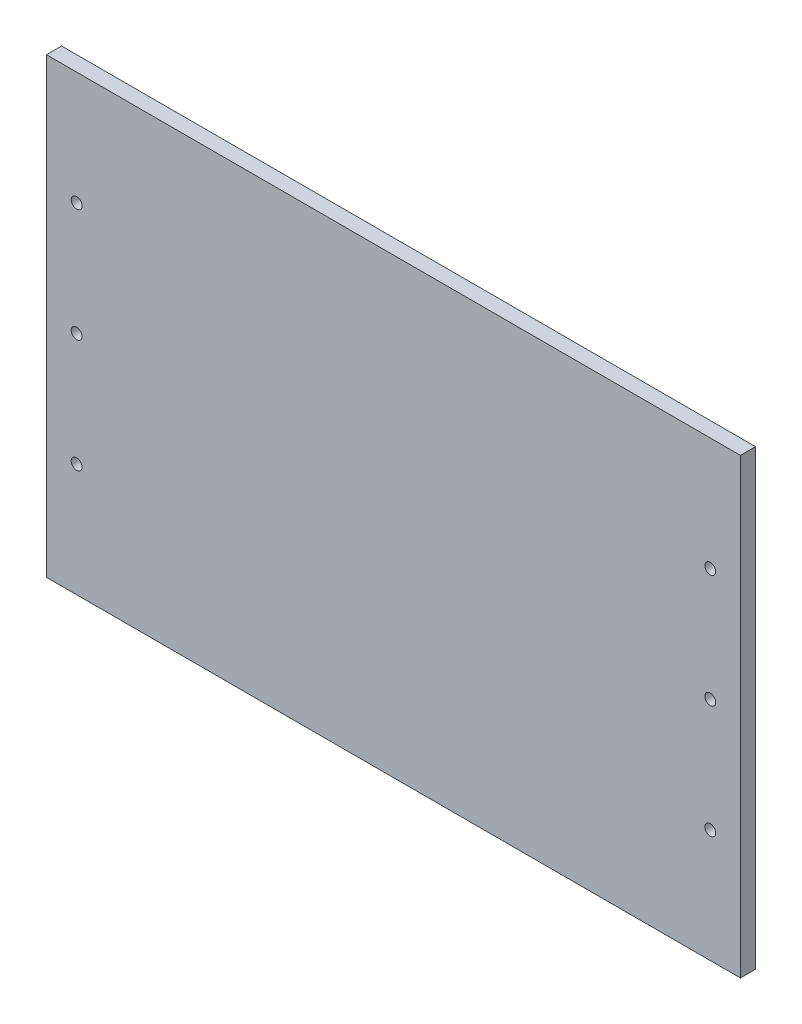
SolidWorks part; units mm, degrees
ref_plane "Płaszczyzna przednia" through (0, 0, 0) normal (0, 0, 1) x (1, 0, 0)
ref_plane "Płaszczyzna górna" through (0, 0, 0) normal (0, 1, 0) x (1, 0, 0)
ref_plane "Płaszczyzna prawa" through (0, 0, 0) normal (1, 0, 0) x (0, 0, -1)
sketch "Szkic1" plane through (0, 0, 0) normal (0, 0, 1) x (1, 0, 0)
  line L1 (-115, -75) -> (115, -75)
  line L2 (-115, -75) -> (-115, 75)
  line L3 (-115, 75) -> (115, 75)
  line L4 (115, -75) -> (115, 75)
  line L5 (0, 75) -> (0, -75) construction
  line L6 (-115, 0) -> (115, 0) construction
  point P0 (0, 0)
  dimension "D1" = 230
  dimension "D2" = 150
extrude "Dodanie-wyciągnięcie1" add sketch "Szkic1" along normal blind 5
sketch "Szkic3" plane through (0, 0, 0) normal (0, 0, -1) x (-1, 0, 0)
  line L0 (0, 75) -> (0, -75) construction
  line L1 (-115, 75) -> (115, 75) construction
  line L2 (115, -75) -> (-115, -75) construction
  point P0 (105, 37.5)
  point P1 (105, 0)
  point P3 (105, -37.5)
  point P15 (-105, -37.5)
  point P16 (-105, 0)
  point P17 (-105, 37.5)
hole_wizard "Pogłębienie walcowe pod M3 Śrubę z łbem stożkowym ściętym1" positions "Szkic3" profile "Szkic4" counterbore size "M3" standard "DIN"
sketch "Szkic4" plane through (-105, 37.5, 0) normal (1, 0, 0) x (0, 1, 0)
  line L0 (0, 0) -> (0, 7.7815)
  line L1 (0, 7.7815) -> (1.8, 6.7)
  line L2 (1.8, 6.7) -> (1.8, 2.4)
  line L3 (1.8, 2.4) -> (3.5, 2.4)
  line L4 (3.5, 2.4) -> (3.5, 0)
  line L5 (3.5, 0) -> (0, 0)
  line L10 (0, 7.7815) -> (-1.8, 6.7) construction
  line L11 (0, -6.35) -> (0, 107.95) construction
  dimension "Średnica otworu" = 3.6
  dimension "Głębokość otworu" = 6.7
  dimension "Średnica pogłębienia walcowego" = 7
  dimension "Głębokość pogłębienia walcowego" = 2.4
  dimension "Kąt wiertła" = 118
